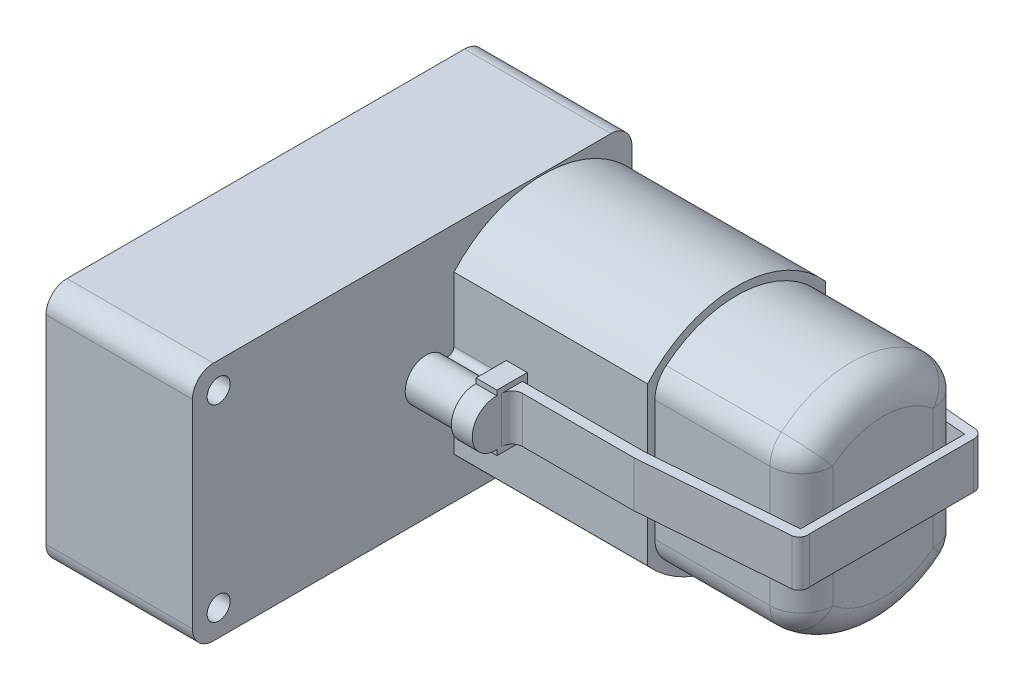
SolidWorks part; units mm, degrees
ref_plane "Front Plane" through (0, 0, 0) normal (0, 0, 1) x (1, 0, 0)
ref_plane "Top Plane" through (0, 0, 0) normal (0, 1, 0) x (1, 0, 0)
ref_plane "Right Plane" through (0, 0, 0) normal (1, 0, 0) x (0, 0, -1)
sketch "Sketch1" plane through (0, 0, 0) normal (0, 1, 0) x (1, 0, 0)
  line L1 (-21.7296, 20.5432) -> (-7.7296, 20.5432)
  line L2 (-21.7296, 20.5432) -> (-21.7296, -21.4568)
  line L3 (-21.7296, -21.4568) -> (-7.7296, -21.4568)
  line L4 (-7.7296, 20.5432) -> (-7.7296, -21.4568)
  dimension "D1" = 42
  dimension "D2" = 14
extrude "Main Body" add sketch "Sketch1" along normal blind 23
fillet "Fillet1" radius 2 4 edges at (-14.7296, 23, -20.5432) (-14.7296, 0, -20.5432) (-14.7296, 0, 21.4568) (-14.7296, 23, 21.4568)
sketch "Sketch2" plane through (-7.7296, 0, 0) normal (1, 0, 0) x (0, 0, -1)
  line L2 (3.5432, 19.0333) -> (3.5432, 3.9667)
  line L4 (20.5432, 19.0333) -> (20.5432, 3.9667)
  line L5 (20.5432, 21) -> (20.5432, 2) construction
  line L6 (-996.4568, 11.5) -> (49003.5432, 11.5) construction
  line L7 (12.0432, -977) -> (12.0432, 49023) construction
  arc A0 (20.5432, 19.0333) -> (3.5432, 19.0333) centre (12.0432, 11.5) ccw
  arc A1 (3.5432, 3.9667) -> (20.5432, 3.9667) centre (12.0432, 11.5) ccw
  point P11 (3.5432, 11.5)
extrude "Motor Holder" add sketch "Sketch2" along normal blind 18.5
sketch "Sketch3" plane through (-7.7296, 0, 0) normal (1, 0, 0) x (0, 0, -1)
  line L0 (3.5432, 11.5) -> (-4.3884, 11.5) construction
  line L1 (3.5432, 19.0333) -> (3.5432, 3.9667) construction
  line L2 (3.5432, 19.0333) -> (3.5432, 3.9667) construction
  line L3 (3.5432, 12.8669) -> (3.5432, 10.3277)
  arc A0 (2.5583, 12.5817) -> (2.6054, 10.4953) centre (0.876, 11.5) ccw
  arc A1 (2.5583, 12.5817) -> (3.5432, 12.8669) centre (3.0065, 12.8772) ccw
  arc A2 (2.6054, 10.4953) -> (3.5432, 10.3277) centre (3.0401, 10.2201) cw
extrude "Boss-Extrude3" add sketch "Sketch3" along normal blind 5
sketch "Sketch4" plane through (-7.7296, 0, 0) normal (1, 0, 0) x (0, 0, -1)
  line L0 (-18.9568, -979.1157) -> (-18.9568, 49020.8843) construction
  line L1 (-19.4568, 23) -> (18.5432, 23) construction
  line L2 (-21.4568, 21) -> (-21.4568, 2) construction
  line L3 (-19.4568, 0) -> (18.5432, 0) construction
  circle A0 centre (-18.9568, 20.5) radius 1.1
  circle A1 centre (-18.9568, 2.5) radius 1.1
  dimension "D1" = 2.5
  dimension "D2" = 2.5
  dimension "D3" = 2.5
extrude "Nut Holes" cut sketch "Sketch4" against normal blind 15
sketch "Sketch5" plane through (0, 0, -20.5432) normal (0, 0, -1) x (-1, 0, 0)
  line L0 (7.7296, 19.0333) -> (7.7296, 3.9667) construction
  line L2 (6.7296, 9.5) -> (8.7296, 9.5)
  line L3 (6.7296, 9.5) -> (6.7296, 13.5)
  line L4 (6.7296, 13.5) -> (8.7296, 13.5)
  line L5 (8.7296, 9.5) -> (8.7296, 13.5)
  line L6 (6.7296, 9.5) -> (8.7296, 13.5) construction
  line L7 (6.7296, 13.5) -> (8.7296, 9.5) construction
  point P4 (7.7296, 11.5)
  dimension "D1" = 2
  dimension "D2" = 4
extrude "Boss-Extrude4" add sketch "Sketch5" along normal blind 5
sketch "Sketch6" plane through (-6.7296, 0, 0) normal (1, 0, 0) x (0, 0, -1)
  line L0 (25.5432, 13.5) -> (25.5432, 9.5) construction
  line L1 (20.5432, 3.9667) -> (20.5432, 19.0333) construction
  line L2 (20.5432, 13.5) -> (20.5432, 9.5) construction
  circle A0 centre (23.5432, 11.5) radius 2
  arc A1 (21.6793, 12.2253) -> (20.5432, 12.2253) centre (21.1113, 12.3852) cw
  arc A2 (21.6793, 10.7747) -> (20.5432, 10.7747) centre (21.1113, 10.5279) ccw
  line M1 (20.5432, 13.5) -> (20.5432, 9.5)
extrude "Boss-Extrude5" add sketch "Sketch6" along normal up to vertex (4 mm away) contours A0 A1 | A2 A0 A1 M1
sketch "Sketch7" plane through (-6.7296, 0, 0) normal (1, 0, 0) x (0, 0, -1)
  line L0 (23.5432, 13.5) -> (23.5432, 13.9672)
  line L1 (23.5432, 13.9672) -> (25.7602, 13.9672)
  line L2 (25.7602, 13.9672) -> (25.7602, 8.9705)
  line L3 (25.7602, 8.9705) -> (23.5432, 8.9705)
  line L4 (23.5432, 8.9705) -> (23.5432, 9.5)
  arc A0 (23.5432, 13.5) -> (23.5432, 9.5) centre (23.5432, 11.5) cw
  arc A1 (21.6793, 10.7747) -> (21.6793, 12.2253) centre (23.5432, 11.5) ccw construction
  arc A2 (23.5432, 9.5) -> (25.5432, 11.5) centre (23.5432, 11.5) ccw construction
extrude "Cut-Extrude2" cut sketch "Sketch7" against normal blind 2
sketch "Sketch8" plane through (10.7704, 0, 0) normal (1, 0, 0) x (0, 0, -1)
  line L0 (4.2432, 17.3565) -> (4.2432, 5.8225)
  line L2 (19.8432, 5.8225) -> (19.8432, 17.3565)
  line L4 (3.5432, 19.0333) -> (3.5432, 3.9667) construction
  line L5 (20.5432, 3.9667) -> (20.5432, 19.0333) construction
  arc A0 (5.324, 3.5167) -> (18.7624, 3.5167) centre (12.0432, 11.5895) ccw
  arc A1 (18.7624, 19.6623) -> (5.324, 19.6623) centre (12.0432, 11.5895) ccw
  arc A2 (4.2432, 17.3565) -> (5.324, 19.6623) centre (7.2432, 17.3565) cw
  arc A3 (19.8432, 17.3565) -> (18.7624, 19.6623) centre (16.8432, 17.3565) ccw
  arc A4 (4.2432, 5.8225) -> (5.324, 3.5167) centre (7.2432, 5.8225) ccw
  arc A5 (18.7624, 3.5167) -> (19.8432, 5.8225) centre (16.8432, 5.8225) ccw
  point P11 (4.2432, 11.5895)
  dimension "D3" = 3
  dimension "D1" = 0.7
  dimension "D2" = 0.7
extrude "Boss-Extrude6" add sketch "Sketch8" along normal blind 14
sketch "Sketch9" plane through (-2.7296, 0, 0) normal (1, 0, 0) x (0, 0, -1)
  line L0 (3.5432, 8.7842) -> (0.6451, 14.2207) construction
  line L1 (20.5342, 8.7842) -> (23.4323, 8.7842)
  line L2 (20.5342, 8.7842) -> (20.5342, 14.2207)
  line L3 (20.5342, 14.2207) -> (23.4323, 14.2207)
  line L4 (23.4323, 8.7842) -> (23.4323, 9.2638)
  line L5 (20.5342, 8.7842) -> (23.4323, 14.2207) construction
  line L6 (20.5342, 14.2207) -> (23.4323, 8.7842) construction
  line L7 (3.5432, 14.2207) -> (0.6451, 8.7842) construction
  line L8 (3.5432, 8.7842) -> (0.6451, 8.7842)
  line L9 (0.6451, 14.2207) -> (0.6451, 13.741)
  line L10 (3.5432, 14.2207) -> (3.5432, 8.7842)
  line L11 (3.5432, 14.2207) -> (0.6451, 14.2207)
  line L12 (0.6451, 9.2942) -> (0.6451, 8.7842)
  line L13 (23.4323, 13.7107) -> (23.4323, 14.2207)
  arc A0 (23.4323, 13.7107) -> (23.4323, 9.2638) centre (23.5637, 11.4873) cw
  arc A1 (0.6451, 9.2942) -> (0.6451, 13.741) centre (0.5138, 11.5176) cw
  point P0 (21.9833, 11.5024)
  point P8 (2.0942, 11.5024)
  arc M1 (21.6793, 10.7747) -> (21.6793, 12.2253) centre (23.5432, 11.5) ccw
  arc M2 (21.6793, 12.2253) -> (20.5432, 12.2253) centre (21.1113, 12.3852) cw
  line M3 (20.5432, 12.2253) -> (20.5432, 10.7747)
  arc M4 (20.5432, 10.7747) -> (21.6793, 10.7747) centre (21.1113, 10.5279) cw
extrude "Boss-Extrude7" add sketch "Sketch9" along normal blind 2 contours A0 L4 M1 | L4 M1 | L1 L4 L3 L2 M1 M4 M3 M2 | L4 M1 M2 M3 M4 | A1 L12 L8 L10 L11 L9
fillet "Fillet2" radius 3 8 edges at (24.7704, 18.6297, -19.5596) (24.7704, 11.5895, -19.8432) (24.7704, 4.5492, -19.5596) (24.7704, 1.0863, -12.0432) (24.7704, 4.5492, -4.5268) (24.7704, 11.5895, -4.2432) (24.7704, 18.6297, -4.5268) (24.7704, 22.0927, -12.0432)
sketch3d "3DSketch2" plane through (0, 0, 0) normal (0, 0, 1) x (1, 0, 0)
  dimension "D1" = 11.5176
sketch "Sketch10" plane through (0, 11.5176, 0) normal (0, 1, 0) x (1, 0, 0)
  line L0 (-0.7296, 20.5432) -> (-0.7296, 23.4323) construction
  line L1 (-0.7296, 21.9878) -> (10.9103, 21.9878)
  line L2 (-0.7296, 21.9878) -> (-0.7296, 21.0215)
  line L3 (-0.7296, 21.0215) -> (10.9103, 21.0215)
  line L5 (-0.7296, 3.5432) -> (-0.7296, 0.6451) construction
  line L6 (-0.7296, 2.0942) -> (10.9103, 2.0942)
  line L7 (-0.7296, 2.0942) -> (-0.7296, 3.0856)
  line L8 (-0.7296, 3.0856) -> (10.9103, 3.0856)
  line L10 (24.7704, 19.8432) -> (10.9103, 21.0215)
  line L12 (24.7704, 19.8432) -> (24.7704, 4.1661)
  line L14 (25.6047, 19.8432) -> (25.6047, 4.1661)
  line L15 (10.9103, 21.9878) -> (24.7704, 20.8094)
  line L17 (10.9103, 3.0856) -> (24.7704, 4.1661)
  line L18 (10.9103, 2.0942) -> (24.9385, 3.1877)
  arc A0 (24.9385, 3.1877) -> (25.6047, 4.1661) centre (24.7903, 4.0047) ccw
  arc A1 (24.7704, 20.8094) -> (25.6047, 19.8432) centre (24.7158, 19.919) cw
extrude "Boss-Extrude8" add sketch "Sketch10" along normal blind 2.2 and the other way blind 2.2
fillet "Fillet3" radius 1 2 edges at (-0.7296, 11.5176, -2.0942) (-0.7296, 11.5176, -21.9878)
sketch "Sketch12" plane through (-21.7296, 0, 0) normal (-1, 0, 0) x (0, 0, 1)
  line L0 (21.4568, 11.5) -> (10.4568, 11.5) construction
  line L1 (21.4568, 21) -> (21.4568, 2) construction
  circle A0 centre (10.4568, 11.5) radius 3.5
  circle A1 centre (10.4568, 11.5) radius 3.0703
extrude "Boss-Extrude9" add sketch "Sketch12" along normal blind 1
sketch "Sketch14" plane through (-21.7296, 0, 0) normal (-1, 0, 0) x (0, 0, 1)
  circle A0 centre (10.4568, 11.5) radius 3
extrude "Boss-Extrude10" add sketch "Sketch14" along normal blind 1
sketch "Sketch15" plane through (-22.7296, 0, 0) normal (-1, 0, 0) x (0, 0, 1)
  line L2 (8.8483, 8.9677) -> (8.8483, 14.0323)
  line L4 (12.0653, 8.9677) -> (12.0653, 14.0323)
  line L5 (8.8483, 8.9677) -> (12.0653, 14.0323) construction
  line L6 (8.8483, 14.0323) -> (12.0653, 8.9677) construction
  circle A0 centre (10.4568, 11.5) radius 3 construction
  arc A1 (8.8483, 14.0323) -> (12.0653, 14.0323) centre (10.4568, 11.5) cw
  arc A2 (8.8483, 8.9677) -> (12.0653, 8.9677) centre (10.4568, 11.5) ccw
  circle A3 centre (10.4568, 11.5) radius 1
  point P0 (10.4568, 11.5)
  point P1 (10.4568, 11.5)
extrude "Shaft" add sketch "Sketch15" along normal blind 7
sketch "Sketch16" plane through (-21.7296, 0, 0) normal (-1, 0, 0) x (0, 0, 1)
  line L0 (21.4568, 11.5) -> (-0.5432, 11.5) construction
  line L1 (21.4568, 21) -> (21.4568, 2) construction
  circle A0 centre (-0.5432, 11.5) radius 2
extrude "Boss-Extrude12" add sketch "Sketch16" along normal blind 1.5
